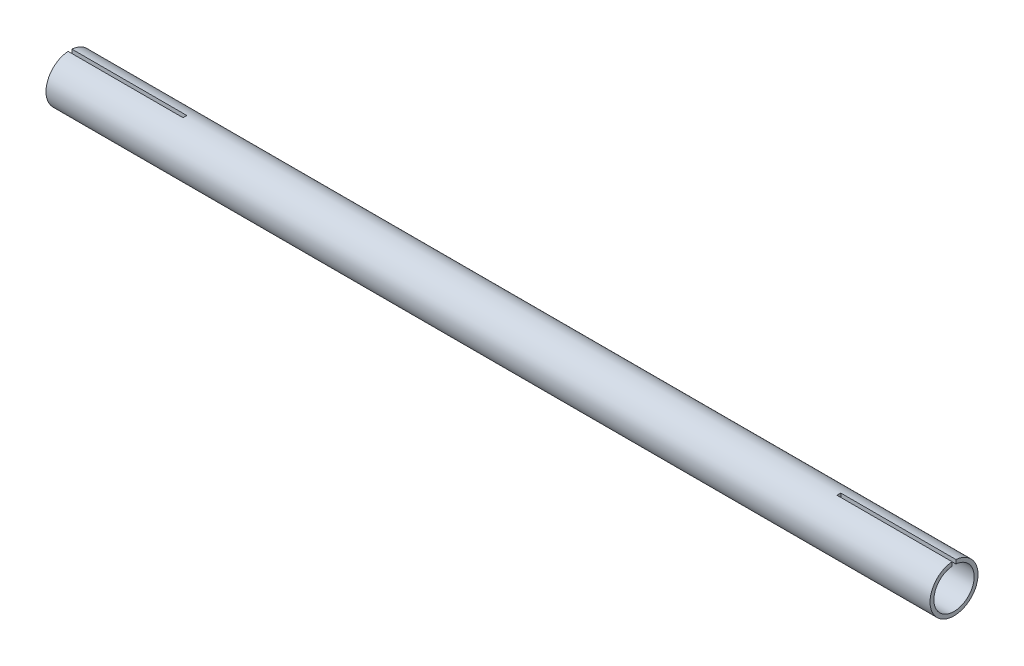
SolidWorks part; units mm, degrees
material "Alumina"
ref_plane "Plano frontal" through (0, 0, 0) normal (0, 0, 1) x (1, 0, 0)
ref_plane "Plano superior" through (0, 0, 0) normal (0, 1, 0) x (1, 0, 0)
ref_plane "Plano direito" through (0, 0, 0) normal (1, 0, 0) x (0, 0, -1)
sketch "Esboço2" plane through (0, 0, 0) normal (1, 0, 0) x (0, 0, -1)
  circle A0 centre (0, 0) radius 12.5
  circle A1 centre (0, 0) radius 10.5
  dimension "D1" = 25
  dimension "D2" = 2
extrude "Ressalto-extrusão1" add sketch "Esboço2" along normal mid plane 461
sketch "Esboço3" plane through (230.5, 0, 0) normal (1, 0, 0) x (0, 0, -1)
  line L0 (0, 0) -> (0, 12.5) construction
  line L6 (1, 15) -> (-1, 15)
  line L7 (1, 15) -> (1, 10)
  line L8 (1, 10) -> (-1, 10)
  line L9 (-1, 15) -> (-1, 10)
  line L10 (1, 15) -> (-1, 10) construction
  line L11 (1, 10) -> (-1, 15) construction
  circle A1 centre (0, 0) radius 12.5 construction
  dimension "D1" = 2
  dimension "D2" = 5
extrude "Corte-extrusão1" cut sketch "Esboço3" against normal blind 60
mirror "Espelhar1" about plane through (0, 0, 0) normal (1, 0, 0) of "Corte-extrusão1"
